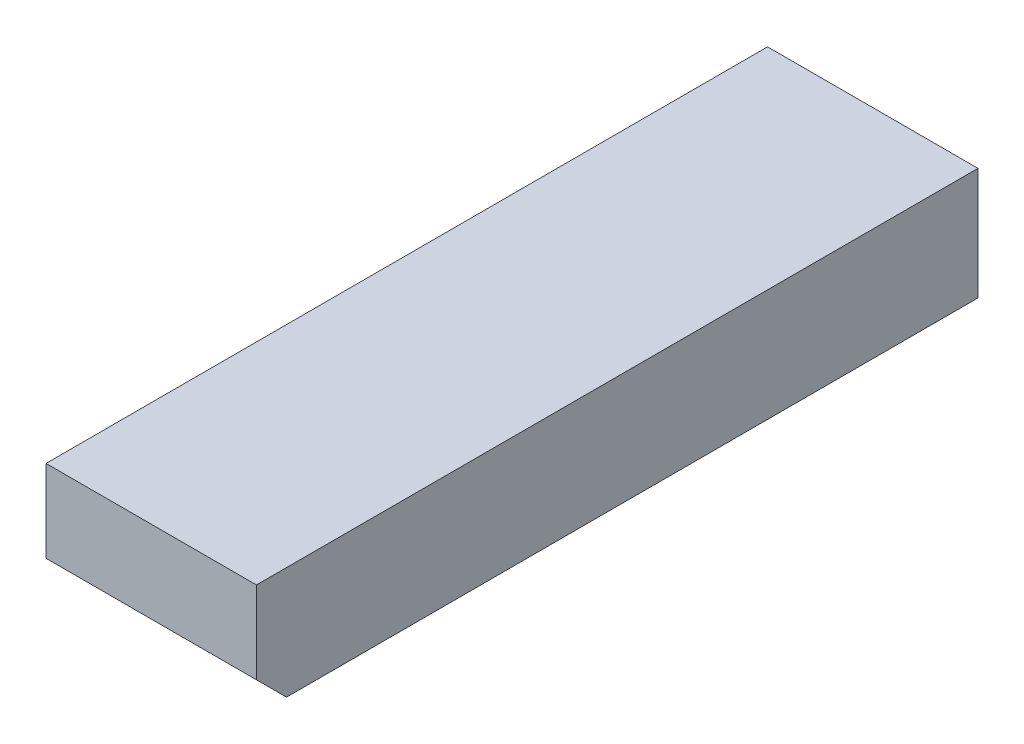
SolidWorks part; units mm, degrees
ref_plane "Front Plane" through (0, 0, 0) normal (0, 0, 1) x (1, 0, 0)
ref_plane "Top Plane" through (0, 0, 0) normal (0, 1, 0) x (1, 0, 0)
ref_plane "Right Plane" through (0, 0, 0) normal (1, 0, 0) x (0, 0, -1)
sketch "Sketch1" plane through (0, 0, 0) normal (0, 0, 1) x (1, 0, 0)
  line L1 (0, 0) -> (26.67, 0)
  line L2 (0, 0) -> (0, 14.224)
  line L3 (0, 14.224) -> (26.67, 14.224)
  line L4 (26.67, 0) -> (26.67, 14.224)
  dimension "D1" = 14.224
  dimension "D2" = 26.67
extrude "Boss-Extrude1" add sketch "Sketch1" along normal blind 91.44
chamfer "Chamfer1" distance 3.81 angle 45 1 edges at (13.335, 0, 91.44)
